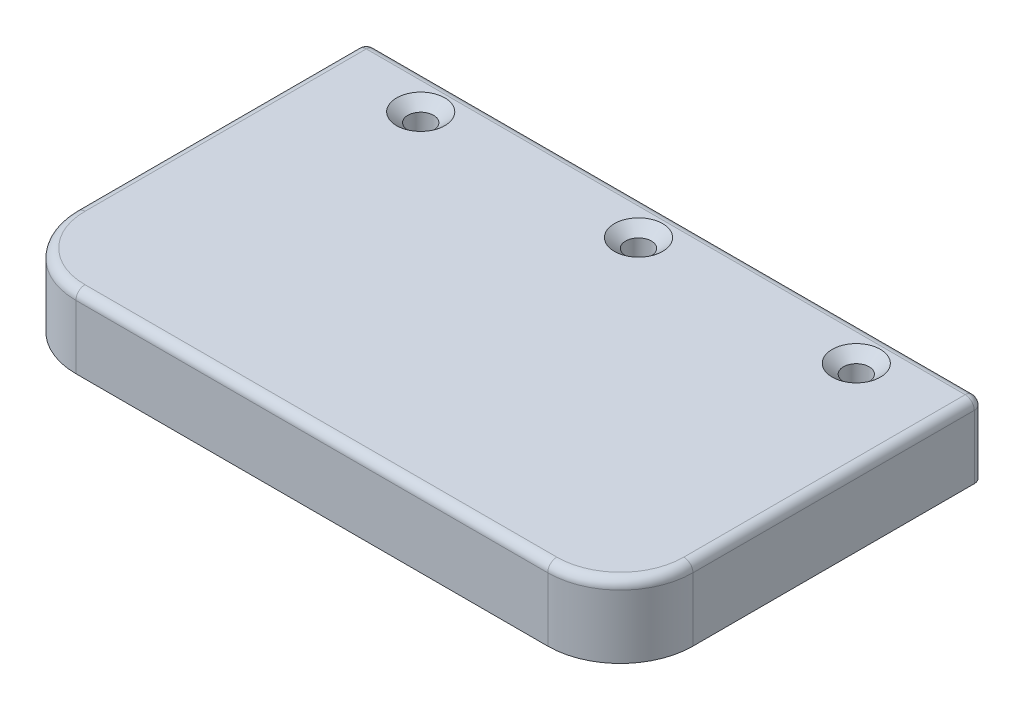
SolidWorks part; units mm, degrees
material "PE High Density"
ref_plane "Front Plane" through (0, 0, 0) normal (0, 0, 1) x (1, 0, 0)
ref_plane "Top Plane" through (0, 0, 0) normal (0, 1, 0) x (1, 0, 0)
ref_plane "Right Plane" through (0, 0, 0) normal (1, 0, 0) x (0, 0, -1)
sketch "Sketch1" plane through (0, 0, 0) normal (0, 0, 1) x (1, 0, 0)
  line L1 (-53.975, -6.35) -> (53.975, -6.35)
  line L2 (-53.975, -6.35) -> (-53.975, 6.35)
  line L3 (-53.975, 6.35) -> (53.975, 6.35)
  line L4 (53.975, -6.35) -> (53.975, 6.35)
  line L5 (-53.975, -6.35) -> (53.975, 6.35) construction
  line L6 (-53.975, 6.35) -> (53.975, -6.35) construction
  point P0 (0, 0)
  dimension "D1" = 12.7
  dimension "D2" = 107.95
extrude "Boss-Extrude1" add sketch "Sketch1" along normal mid plane 63.5
fillet "Fillet1" radius 12.7 2 edges at (-53.975, 0, 31.75) (53.975, 0, 31.75)
hole_wizard "CSK for #8 Flat Head Machine Screw (100)1" positions "Sketch2" profile "Sketch3" countersink size "#8" standard "ANSI Inch"
sketch "Sketch2" plane through (0, 6.35, 0) normal (0, 1, 0) x (1, 0, 0)
  line L0 (53.975, 31.75) -> (-53.975, 31.75) construction
  point P0 (-38.1, 25.4)
  point P2 (38.1, 25.4)
  point P8 (0, 25.4)
  point P11 (0, 0)
  dimension "D1" = 6.35
  dimension "D2" = 38.1
  dimension "D3" = 38.1
sketch "Sketch3" plane through (-38.1, 6.35, -25.4) normal (1, 0, 0) x (0, 0, 1)
  line L0 (0, 0) -> (0, 20.4007)
  line L1 (0, 20.4007) -> (2.2479, 19.05)
  line L2 (2.2479, 19.05) -> (2.2479, 1.6518)
  line L3 (2.2479, 1.6518) -> (4.2164, 0)
  line L5 (4.2164, 0) -> (0, 0)
  line L6 (-2.2479, 1.6518) -> (-4.2164, 0) construction
  line L10 (0, 20.4007) -> (-2.2479, 19.05) construction
  line L11 (0, -6.35) -> (0, 107.95) construction
  dimension "Hole Dia." = 4.4958
  dimension "Hole Depth" = 19.05
  dimension "Near C'Sink Dia." = 8.4328
  dimension "Near C'Sink Angle" = 100
  dimension "Drill Angle" = 118
fillet "Fillet2" radius 1.5875 8 edges at (53.975, 6.35, -6.35) (50.2553, 6.35, 28.0303) (-53.975, 6.35, -6.35) (-50.2553, 6.35, 28.0303) (0, 6.35, 31.75) (0, 6.35, -31.75) (-53.975, 0, -31.75) (53.975, 0, -31.75)
equation "\"D3@Sketch2\"=\"D2@Sketch2\""
